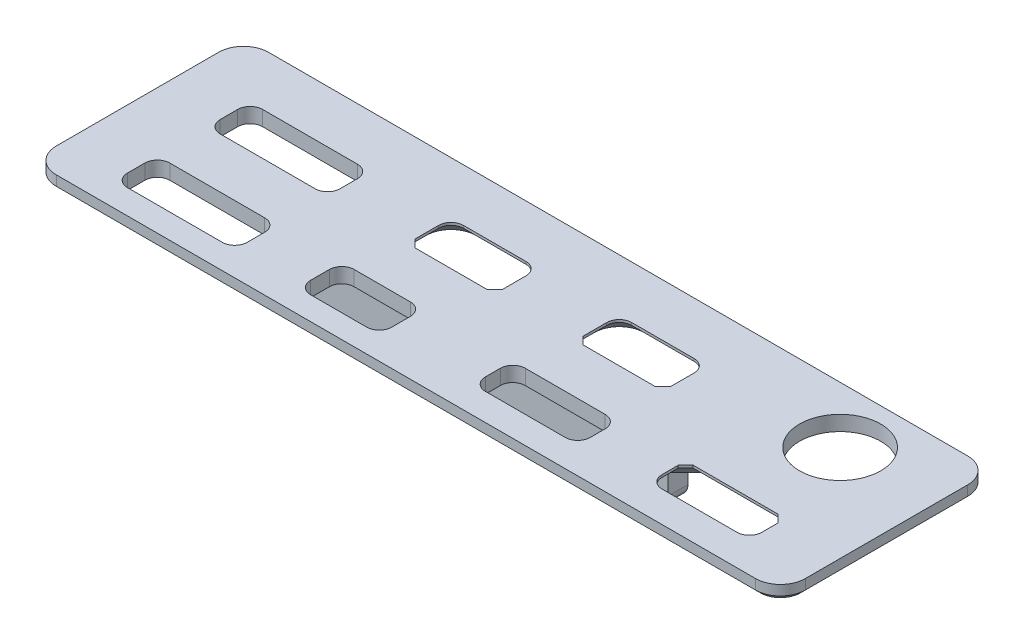
SolidWorks part; units mm, degrees
ref_plane "前视基准面" through (0, 0, 0) normal (0, 0, 1) x (1, 0, 0)
ref_plane "上视基准面" through (0, 0, 0) normal (0, 1, 0) x (1, 0, 0)
ref_plane "右视基准面" through (0, 0, 0) normal (1, 0, 0) x (0, 0, -1)
sketch "草图1" plane through (0, 0, 0) normal (0, 1, 0) x (1, 0, 0)
  line L1 (-30, 8.5) -> (30, 8.5)
  line L2 (-30, 8.5) -> (-30, -8.5)
  line L3 (-30, -8.5) -> (30, -8.5)
  line L4 (30, 8.5) -> (30, -8.5)
  line L5 (-30, 8.5) -> (30, -8.5) construction
  line L6 (-30, -8.5) -> (30, 8.5) construction
  point P0 (0, 0)
  dimension "D1" = 60
  dimension "D2" = 17
extrude "凸台-拉伸1" add sketch "草图1" along normal blind 1.2
sketch "草图4" plane through (0, 1.2, 0) normal (0, 1, 0) x (1, 0, 0)
  line L0 (-30, 8.5) -> (-30, -8.5) construction
  line L1 (-25.2717, 4.3) -> (-15.6717, 4.3)
  line L2 (-25.2717, 4.3) -> (-25.2717, 0.9)
  line L3 (-25.2717, 0.9) -> (-15.6717, 0.9)
  line L4 (-15.6717, 4.3) -> (-15.6717, 0.9)
  line L5 (-9.1829, 4.3) -> (-2.1829, 4.3)
  line L6 (-9.1829, 4.3) -> (-9.1829, 0.8)
  line L7 (-9.1829, 0.8) -> (-2.1829, 0.8)
  line L8 (-2.1829, 4.3) -> (-2.1829, 0.8)
  line L9 (4.2885, 4.3) -> (11.2885, 4.3)
  line L10 (4.2885, 4.3) -> (4.2885, 0.8)
  line L11 (4.2885, 0.8) -> (11.2885, 0.8)
  line L12 (11.2885, 4.3) -> (11.2885, 0.8)
  line L13 (17.05, -3.1348) -> (25.05, -3.1348)
  line L14 (17.05, -3.1348) -> (17.05, -6.0348)
  line L15 (17.05, -6.0348) -> (25.05, -6.0348)
  line L16 (25.05, -3.1348) -> (25.05, -6.0348)
  line L17 (3.2, -3.1348) -> (11.6, -3.1348)
  line L18 (3.2, -3.1348) -> (3.2, -6.3348)
  line L19 (3.2, -6.3348) -> (11.6, -6.3348)
  line L20 (11.6, -3.1348) -> (11.6, -6.3348)
  line L21 (-10.5, -3.1348) -> (-4, -3.1348)
  line L22 (-10.5, -3.1348) -> (-10.5, -6.6348)
  line L23 (-10.5, -6.6348) -> (-4, -6.6348)
  line L24 (-4, -3.1348) -> (-4, -6.6348)
  line L25 (-25.2717, -3.1348) -> (-15.6717, -3.1348)
  line L26 (-25.2717, -3.1348) -> (-25.2717, -6.5348)
  line L27 (-25.2717, -6.5348) -> (-15.6717, -6.5348)
  line L28 (-15.6717, -3.1348) -> (-15.6717, -6.5348)
  line L29 (30, 8.5) -> (-30, 8.5) construction
  line L31 (30, -8.5) -> (30, 8.5) construction
  line L32 (30, 8.5) -> (-30, 8.5) construction
  circle A0 centre (22.2985, 3.9832) radius 3.25
  dimension "D21" = 6.5
  dimension "D1" = 3.5
  dimension "D2" = 6.5
  dimension "D3" = 8.4
  dimension "D4" = 3.2
  dimension "D5" = 9.6
  dimension "D6" = 3.4
  dimension "D7" = 7
  dimension "D8" = 8
  dimension "D9" = 2.9
  dimension "D10" = 4.7283
  dimension "D11" = 7.6
  dimension "D12" = 11.6348
  dimension "D13" = 19.5
  dimension "D14" = 33.2
  dimension "D15" = 4.95
  dimension "D16" = 7
  dimension "D17" = 20.8171
  dimension "D18" = 34.2885
  dimension "D19" = 7.7015
  dimension "D20" = 4.5168
  dimension "D22" = 3.5
extrude "切除-拉伸1" cut sketch "草图4" against normal up to next
fillet "圆角2" radius 1 22 edges at (-25.2717, 0.6, -0.9) (-25.2717, 0.6, -4.3) (-15.6717, 0.6, -0.9) (-15.6717, 0.6, -4.3) (-2.1829, 0.6, -4.3) (-9.1829, 0.6, -4.3) (4.2885, 0.6, -4.3) (11.2885, 0.6, -4.3) (25.05, 0.6, 6.0348) (17.05, 0.6, 6.0348) (11.6, 0.6, 6.3348) (11.6, 0.6, 3.1348) (3.2, 0.6, 3.1348) (3.2, 0.6, 6.3348) (-4, 0.6, 6.6348) (-4, 0.6, 3.1348) (-10.5, 0.6, 3.1348) (-10.5, 0.6, 6.6348) (-15.6717, 0.6, 6.5348) (-15.6717, 0.6, 3.1348) (-25.2717, 0.6, 3.1348) (-25.2717, 0.6, 6.5348)
chamfer "倒角1" distance 0.6 angle 45 6 edges at (-9.1829, 0.6, -0.8) (-2.1829, 0.6, -0.8) (4.2885, 0.6, -0.8) (11.2885, 0.6, -0.8) (17.05, 0.6, 3.1348) (25.05, 0.6, 3.1348)
sketch "草图5" plane through (0, 0, 0) normal (0, -1, 0) x (1, 0, 0)
  line L0 (-30, -8.5) -> (-30, 8.5) construction
  line L1 (-13.9089, -3.3832) -> (-12.4089, -3.3832)
  line L2 (-13.9089, -3.3832) -> (-13.9089, 4.6168)
  line L3 (-13.9089, 4.6168) -> (-12.4089, 4.6168)
  line L4 (-12.4089, -3.3832) -> (-12.4089, 4.6168)
  line L5 (13.0911, -3.3832) -> (14.5911, -3.3832)
  line L6 (13.0911, -3.3832) -> (13.0911, 4.6168)
  line L7 (13.0911, 4.6168) -> (14.5911, 4.6168)
  line L8 (14.5911, -3.3832) -> (14.5911, 4.6168)
  line L9 (30, -8.5) -> (-30, -8.5) construction
  line L10 (30, 8.5) -> (30, -8.5) construction
  dimension "D1" = 1.5
  dimension "D2" = 8
  dimension "D3" = 1.5
  dimension "D4" = 8
  dimension "D5" = 16.0911
  dimension "D6" = 5.1168
  dimension "D7" = 5.1168
  dimension "D8" = 15.4089
extrude "凸台-拉伸2" add sketch "草图5" along normal blind 1.2
sketch "草图6" plane through (0, 0, 0) normal (0, -1, 0) x (1, 0, 0)
  line L0 (-13.9089, 4.6168) -> (-13.9089, -3.3832) construction
  line L1 (-13.9089, 2.1) -> (14.5911, 2.1)
  line L2 (-13.9089, 2.1) -> (-13.9089, 0.5)
  line L3 (-13.9089, 0.5) -> (14.5911, 0.5)
  line L4 (14.5911, 2.1) -> (14.5911, 0.5)
  line L5 (30, -8.5) -> (-30, -8.5) construction
  dimension "D1" = 1.6
  dimension "D2" = 9
extrude "凸台-拉伸3" add sketch "草图6" along normal blind 4
fillet "圆角3" radius 1 2 edges at (14.5911, -4, 1.3) (-13.9089, -4, 1.3)
chamfer "倒角2" distance 1 angle 45 4 edges at (13.8411, -1.2, -3.3832) (-13.1589, -1.2, -3.3832) (13.8411, -1.2, 4.6168) (-13.1589, -1.2, 4.6168)
chamfer "倒角4" distance 1 angle 45 24 edges at (11.2885, 0, -2.35) (10.9956, 0, -4.0071) (7.7885, 0, -4.3) (4.5814, 0, -4.0071) (10.9885, 0, -1.1) (4.2885, 0, -2.35) (4.5885, 0, -1.1) (7.7885, 0, -0.8) (-9.1829, 0, -2.35) (-2.1829, 0, -2.35) (-8.89, 0, -4.0071) (-2.4758, 0, -4.0071) (-5.6829, 0, -4.3) (-2.4829, 0, -1.1) (-8.8829, 0, -1.1) (-5.6829, 0, -0.8) (17.35, 0, 3.4348) (21.05, 0, 3.1348) (24.75, 0, 3.4348) (25.05, 0, 4.3848) (17.05, 0, 4.3848) (24.7571, 0, 5.7419) (17.3429, 0, 5.7419) (21.05, 0, 6.0348)
fillet "圆角4" radius 2 4 edges at (30, 0.6, 8.5) (30, 0.6, -8.5) (-30, 0.6, 8.5) (-30, 0.6, -8.5)
chamfer "倒角5" distance 0.4 angle 45 8 edges at (0, 0, -8.5) (-29.4142, 0, -7.9142) (29.4142, 0, -7.9142) (-30, 0, 0) (30, 0, 0) (-29.4142, 0, 7.9142) (29.4142, 0, 7.9142) (0, 0, 8.5)
